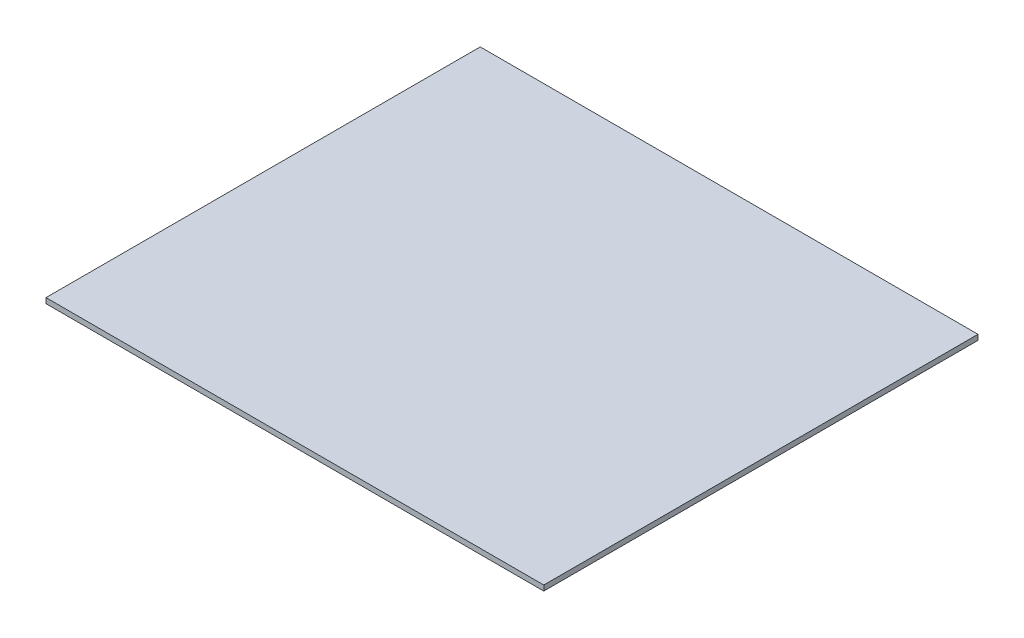
SolidWorks part; units mm, degrees
ref_plane "Front Plane" through (0, 0, 0) normal (0, 0, 1) x (1, 0, 0)
ref_plane "Top Plane" through (0, 0, 0) normal (0, 1, 0) x (1, 0, 0)
ref_plane "Right Plane" through (0, 0, 0) normal (1, 0, 0) x (0, 0, -1)
sketch "Sketch1" plane through (0, 0, 0) normal (0, 1, 0) x (1, 0, 0)
  line L1 (-17.3059, 509.8112) -> (579.5941, 509.8112)
  line L2 (-17.3059, 509.8112) -> (-17.3059, -10.8888)
  line L3 (-17.3059, -10.8888) -> (579.5941, -10.8888)
  line L4 (579.5941, 509.8112) -> (579.5941, -10.8888)
  dimension "D1" = 520.7
  dimension "D2" = 596.9
extrude "Boss-Extrude1" add sketch "Sketch1" along normal blind 6.35
